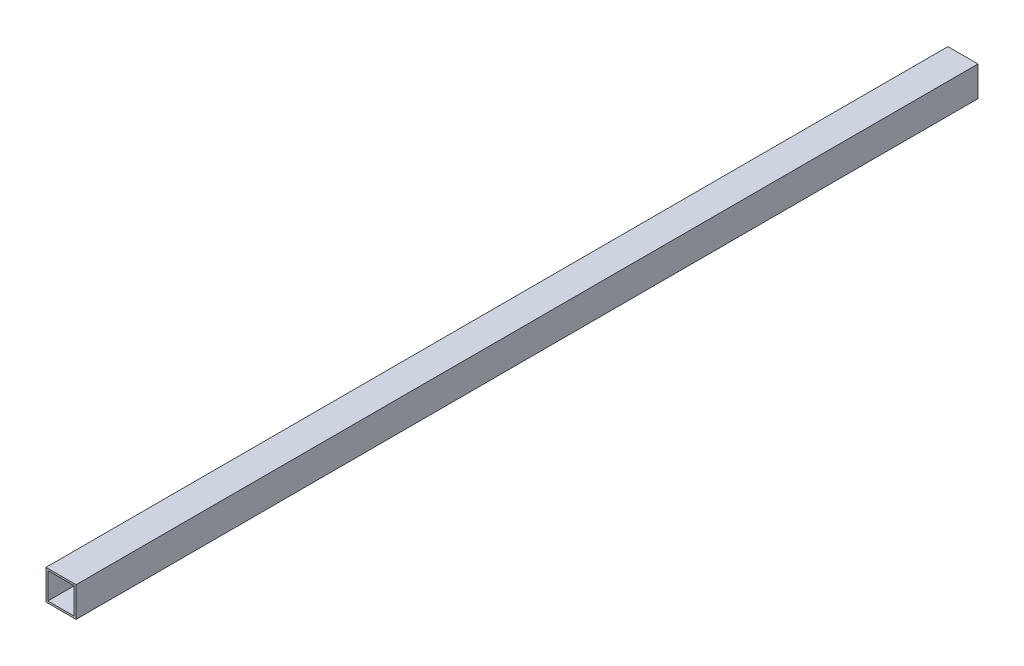
SolidWorks part; units mm, degrees
material "AISI 1020"
ref_plane "Front Plane" through (0, 0, 0) normal (0, 0, 1) x (1, 0, 0)
ref_plane "Top Plane" through (0, 0, 0) normal (0, 1, 0) x (1, 0, 0)
ref_plane "Right Plane" through (0, 0, 0) normal (1, 0, 0) x (0, 0, -1)
sketch "Sketch1" plane through (0, 0, 0) normal (0, 0, 1) x (1, 0, 0)
  line L0 (22.225, 22.225) -> (22.225, 25.4) construction
  line L1 (-25.4, -25.4) -> (25.4, -25.4)
  line L2 (-25.4, -25.4) -> (-25.4, 25.4)
  line L3 (-25.4, 25.4) -> (25.4, 25.4)
  line L4 (25.4, -25.4) -> (25.4, 25.4)
  line L5 (-25.4, -25.4) -> (25.4, 25.4) construction
  line L6 (-25.4, 25.4) -> (25.4, -25.4) construction
  line L7 (-22.225, -22.225) -> (22.225, -22.225)
  line L8 (-22.225, -22.225) -> (-22.225, 22.225)
  line L9 (-22.225, 22.225) -> (22.225, 22.225)
  line L10 (22.225, -22.225) -> (22.225, 22.225)
  line L11 (-22.225, -22.225) -> (22.225, 22.225) construction
  line L12 (-22.225, 22.225) -> (22.225, -22.225) construction
  line L13 (22.225, -22.225) -> (25.4, -22.225) construction
  point P0 (0, 0)
  point P6 (0, 0)
  dimension "D2" = 50.8
  dimension "D3" = 3.175
extrude "Boss-Extrude1" add sketch "Sketch1" along normal blind 1524
